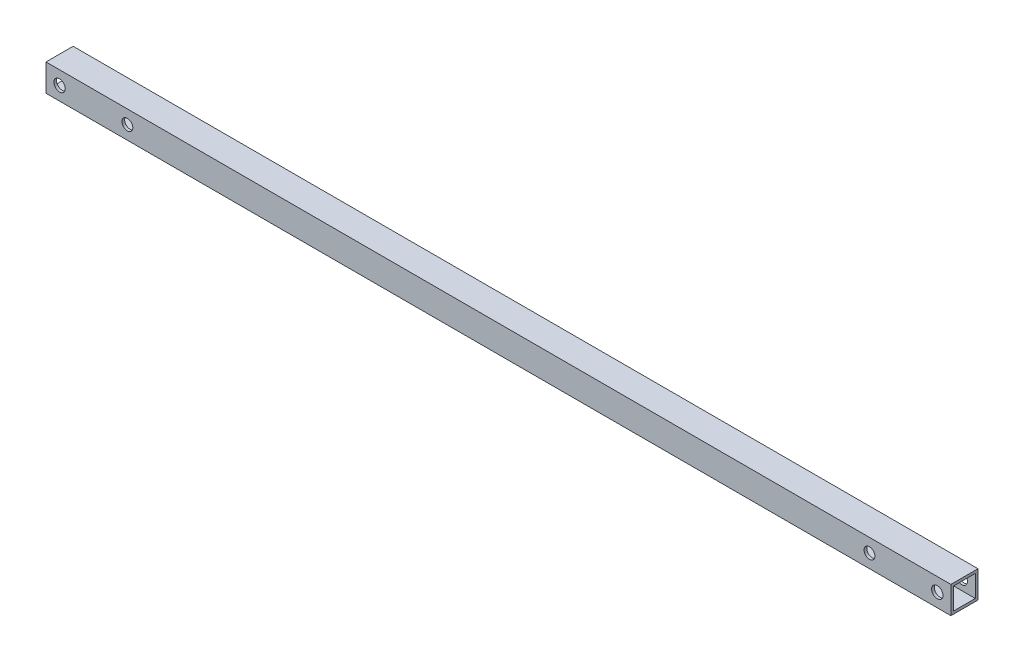
SolidWorks part; units mm, degrees
material "5052-H34"
ref_plane "正面" through (0, 0, 0) normal (0, 0, 1) x (1, 0, 0)
ref_plane "平面" through (0, 0, 0) normal (0, 1, 0) x (1, 0, 0)
ref_plane "右側面" through (0, 0, 0) normal (1, 0, 0) x (0, 0, -1)
sketch "ｽｹｯﾁ1" plane through (0, 0, 0) normal (1, 0, 0) x (0, -1, 0)
  line L1 (-5, 5) -> (5, 5)
  line L2 (-5, 5) -> (-5, -5)
  line L3 (-5, -5) -> (5, -5)
  line L4 (5, 5) -> (5, -5)
  line L5 (-5, 5) -> (5, -5) construction
  line L6 (-5, -5) -> (5, 5) construction
  point P0 (0, 0)
  dimension "D1" = 10
  dimension "D2" = 10
extrude "押し出し-薄板1" add sketch "ｽｹｯﾁ1" along normal blind 333.5448 thin
sketch "ｽｹｯﾁ2" plane through (0, 0, 5) normal (0, 0, 1) x (1, 0, 0)
  line L0 (166.7724, 5) -> (166.7724, -5) construction
  line L1 (333.5448, 5) -> (0, 5) construction
  line L2 (333.5448, -5) -> (0, -5) construction
  line L3 (0, 0) -> (5, 0) construction
  line L4 (5, 0) -> (30, 0) construction
  circle A0 centre (5, 0) radius 2.1
  circle A1 centre (328.5448, 0) radius 2.1
  circle A2 centre (30, 0) radius 2
  circle A3 centre (303.5448, 0) radius 2
  dimension "D2" = 4.2
  dimension "D4" = 4
  dimension "D1" = 5
  dimension "D3" = 25
extrude "ｶｯﾄ - 押し出し1" cut sketch "ｽｹｯﾁ2" against normal through all
equation "\"D1@押し出し-薄板1\"=sqr(232.5^2+225^2)+10"
